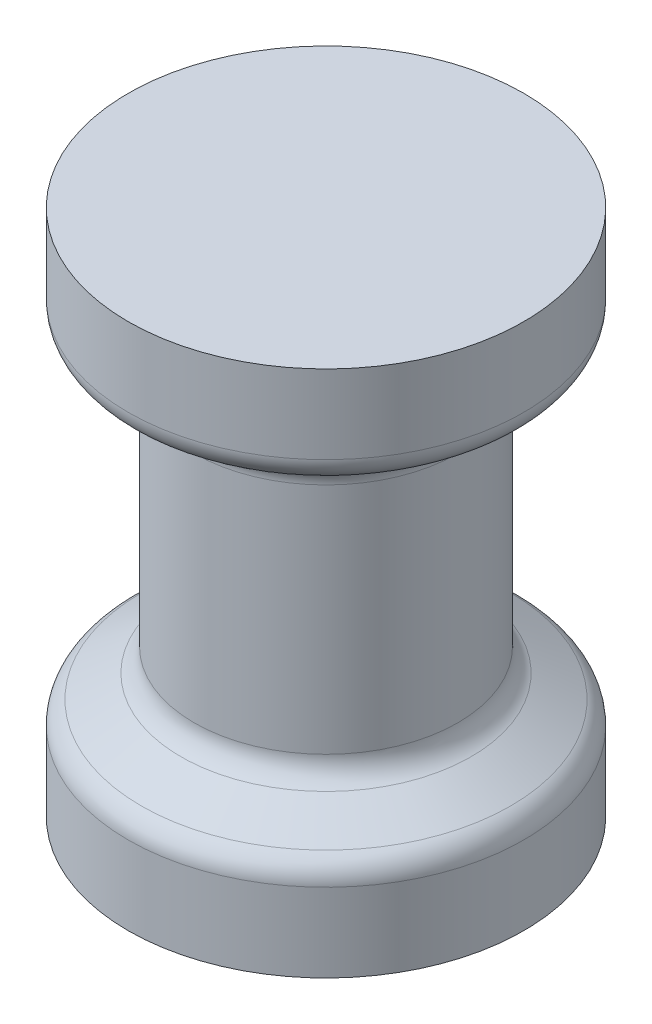
SolidWorks part; units mm, degrees
ref_plane "Front Plane" through (0, 0, 0) normal (0, 0, 1) x (1, 0, 0)
ref_plane "Top Plane" through (0, 0, 0) normal (0, 1, 0) x (1, 0, 0)
ref_plane "Right Plane" through (0, 0, 0) normal (1, 0, 0) x (0, 0, -1)
sketch "Sketch2" plane through (0, 0, 0) normal (1, 0, 0) x (0, 0, -1)
  line L0 (0, -42.375) -> (0, 42.375) construction
  line L1 (0, 10) -> (-7.5, 10)
  line L2 (-7.5, 10) -> (-7.5, 6.4434)
  line L3 (-7.5, 6.4434) -> (-5, 5)
  line L4 (-5, 5) -> (-5, -5)
  line L5 (-49.625, 0) -> (49.625, 0) construction
  line L6 (-7.5, -6.4434) -> (-5, -5)
  line L7 (-7.5, -10) -> (-7.5, -6.4434)
  line L8 (0, -10) -> (-7.5, -10)
  line L9 (0, 10) -> (0, -10)
  point P3 (-8, -20.125)
  point P4 (0, 0)
  point P7 (-7.5, 5)
  point P13 (0, 0)
  point P14 (-7.625, 1.375)
  point P15 (0, 0)
  point P16 (-5, 4.633)
  point P18 (-5, 0)
  dimension "D1" = 7.5
  dimension "D2" = 10
  dimension "D3" = 5
  dimension "D4" = 120
  dimension "D5" = 5
revolve "Revolve1" add sketch "Sketch2" angle 360 about L0
fillet "Fillet1" radius 1 2 edges at (0, -5, -5) (0, 5, -5)
fillet "Fillet2" radius 1 2 edges at (0, -6.4434, -7.5) (0, 6.4434, -7.5)
